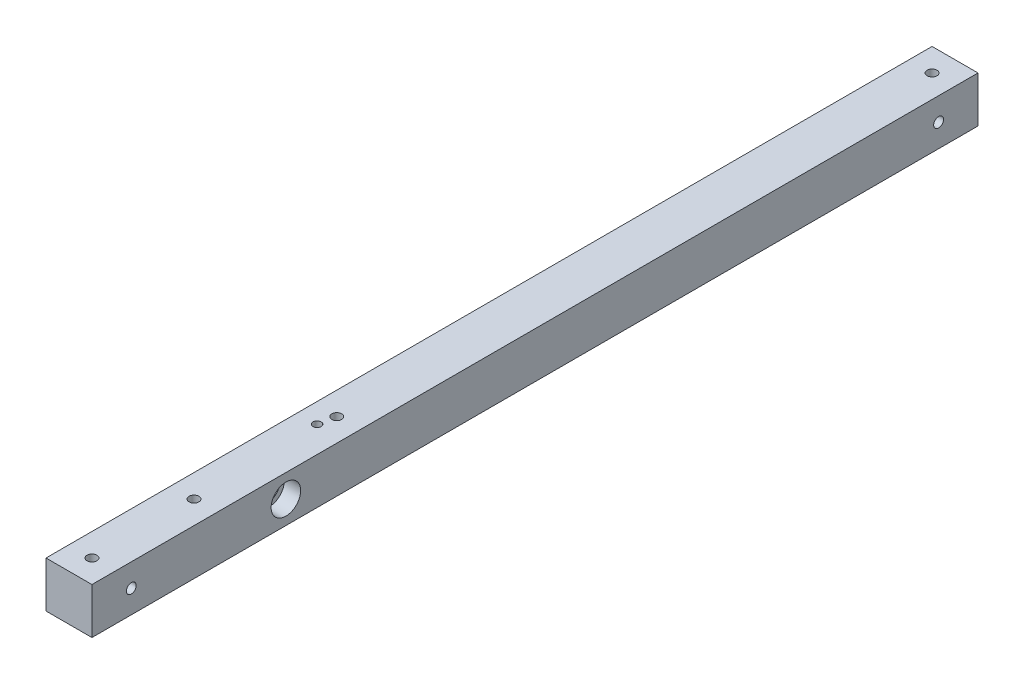
SolidWorks part; units mm, degrees
ref_plane "Ön Düzlem" through (0, 0, 0) normal (0, 0, 1) x (1, 0, 0)
ref_plane "Üst Düzlem" through (0, 0, 0) normal (0, 1, 0) x (1, 0, 0)
ref_plane "Sağ Düzlem" through (0, 0, 0) normal (1, 0, 0) x (0, 0, -1)
sketch "Çizim1" plane through (0, 0, 0) normal (0, 0, 1) x (1, 0, 0)
  line L1 (-14, -14) -> (14, -14)
  line L2 (-14, -14) -> (-14, 14)
  line L3 (-14, 14) -> (14, 14)
  line L4 (14, -14) -> (14, 14)
  line L5 (-14, -14) -> (14, 14) construction
  line L6 (-14, 14) -> (14, -14) construction
  point P0 (0, 0)
  dimension "D1" = 28
  dimension "D2" = 28
extrude "Yükseklik-Ekstrüzyon1" add sketch "Çizim1" along normal mid plane 540
sketch "Çizim3" plane through (0, -14, 0) normal (0, -1, 0) x (1, 0, 0)
  line L0 (-14, 524.2458) -> (14, 524.2458) construction
  line L1 (-14, 270) -> (-14, -270) construction
  line L2 (14, 270) -> (14, -270) construction
  line L3 (-14, -270) -> (14, -270) construction
  line L4 (14, 270) -> (-14, 270) construction
  circle A0 centre (0, -256) radius 3
  circle A1 centre (0, 256) radius 3
  point P11 (0, 524.2458)
  dimension "D1" = 14
  dimension "D3" = 6
  dimension "D2" = 14
extrude "Kes-Ekstrüzyon2" cut sketch "Çizim3" against normal through all
sketch "Çizim4" plane through (0, -14, 0) normal (0, -1, 0) x (1, 0, 0)
  circle A0 centre (0, -256) radius 5
  circle A1 centre (0, 256) radius 5
  dimension "D1" = 10
extrude "Kes-Ekstrüzyon3" cut sketch "Çizim4" against normal blind 7
sketch "Çizim5" plane through (14, 0, 0) normal (1, 0, 0) x (0, 0, -1)
  circle A0 centre (-151.8, 0) radius 6
  dimension "D2" = 12
  dimension "D1" = 151.8
extrude "Kes-Ekstrüzyon4" cut sketch "Çizim5" against normal through all
sketch "Çizim6" plane through (14, 0, 0) normal (1, 0, 0) x (0, 0, -1)
  circle A0 centre (-151.8, 0) radius 9
  dimension "D1" = 18
extrude "Kes-Ekstrüzyon5" cut sketch "Çizim6" against normal blind 10
sketch "Çizim7" plane through (-14, 0, 0) normal (-1, 0, 0) x (0, 0, 1)
  line L0 (-270, 14) -> (-270, -14) construction
  line L2 (270, 14) -> (270, -14) construction
  circle A0 centre (-246, 0) radius 3
  circle A1 centre (246, 0) radius 3
  point P8 (-270, 0)
  dimension "D1" = 6
  dimension "D3" = 24
  dimension "D2" = 24
extrude "Kes-Ekstrüzyon6" cut sketch "Çizim7" against normal through all
sketch "Çizim8" plane through (-14, 0, 0) normal (-1, 0, 0) x (0, 0, 1)
  circle A0 centre (-246, 0) radius 5
  circle A1 centre (246, 0) radius 5
  dimension "D1" = 10
extrude "Kes-Ekstrüzyon7" cut sketch "Çizim8" against normal blind 7
sketch "Sketch1" plane through (0, 14, 0) normal (0, 1, 0) x (1, 0, 0)
  line L0 (14, -270) -> (14, 270) construction
  line L1 (14, -270) -> (-14, -270) construction
  circle A0 centre (0, -106.8) radius 3
  circle A1 centre (0, -193.8) radius 3
  dimension "D3" = 6
  dimension "D4" = 6
  dimension "D1" = 14
  dimension "D2" = 14
  dimension "D5" = 76.2
  dimension "D6" = 87
extrude "Cut-Extrude1" cut sketch "Sketch1" against normal blind 10
sketch "Sketch2" plane through (-14, 0, 0) normal (-1, 0, 0) x (0, 0, 1)
  line L0 (270, 14) -> (-270, 14) construction
  line L1 (270, 14) -> (270, -14) construction
  circle A0 centre (116.8, 0) radius 6
  dimension "D2" = 153.2
  dimension "D3" = 12
  dimension "D1" = 14
extrude "Cut-Extrude2" cut sketch "Sketch2" against normal blind 20
sketch "Sketch3" plane through (0, 14, 0) normal (0, 1, 0) x (1, 0, 0)
  line L0 (14, -270) -> (-14, -270) construction
  line L1 (-14, -270) -> (-14, 270) construction
  circle A0 centre (-2, -116.8) radius 2.5
  point P6 (0, 0)
  dimension "D1" = 5
  dimension "D2" = 153.2
  dimension "D3" = 12
extrude "Cut-Extrude3" cut sketch "Sketch3" against normal blind 14
